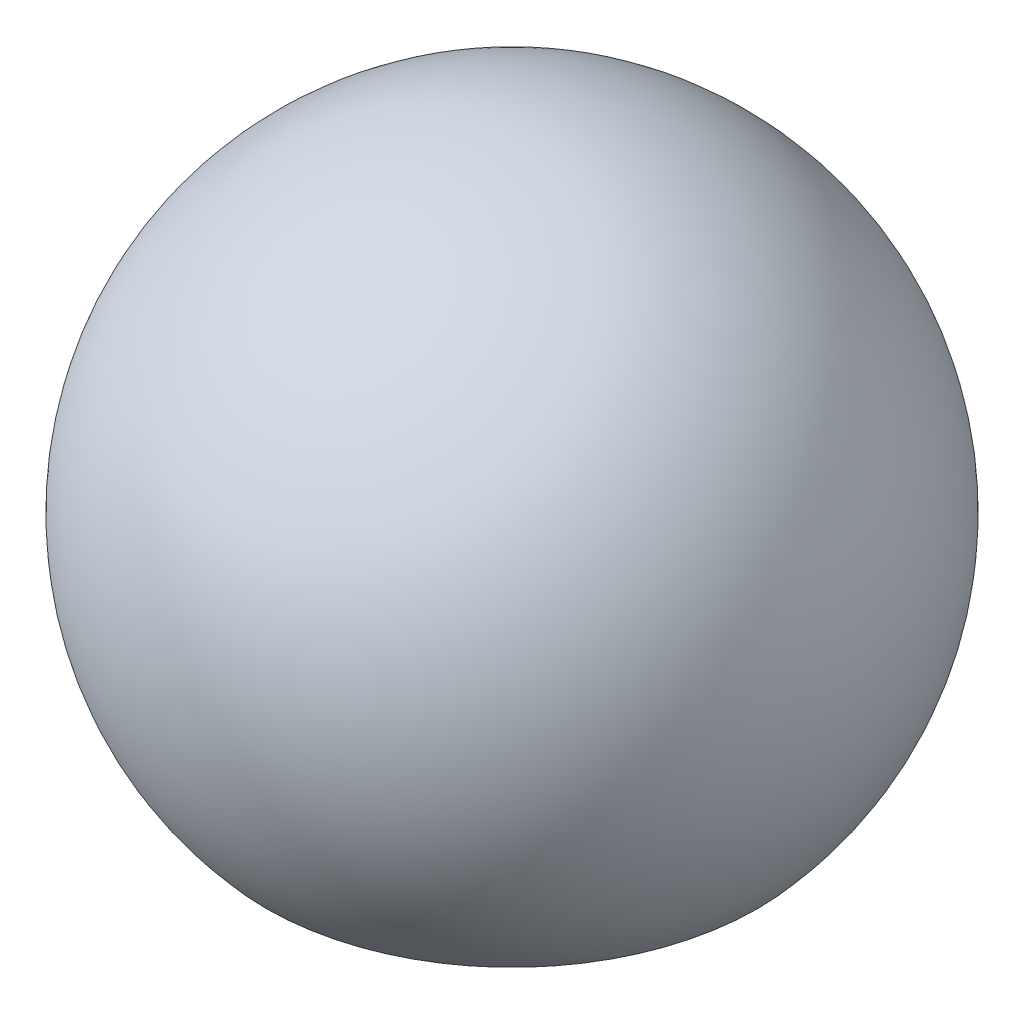
SolidWorks part; units mm, degrees
ref_plane "Front Plane" through (0, 0, 0) normal (0, 0, 1) x (1, 0, 0)
ref_plane "Top Plane" through (0, 0, 0) normal (0, 1, 0) x (1, 0, 0)
ref_plane "Right Plane" through (0, 0, 0) normal (1, 0, 0) x (0, 0, -1)
sketch "Sketch1" plane through (0, 0, 0) normal (0, 0, 1) x (1, 0, 0)
  line L0 (0, 12) -> (0, -8)
  line L1 (-12, 0) -> (12, 0) construction
  line L2 (0, 12) -> (0, -8) construction
  line L3 (0, -8) -> (8.9443, -8)
  arc A0 (8.9443, -8) -> (0, 12) centre (0, 0) ccw
  point P5 (0, 0)
  dimension "D2" = 12
  dimension "D1" = 20
revolve "Revolve1" add sketch "Sketch1" angle 360 about L0
sketch "Sketch2" plane through (0, -8, 0) normal (0, -1, 0) x (1, 0, 0)
  circle A0 centre (0, 0) radius 4
  dimension "D1" = 8
extrude "Cut-Extrude1" cut sketch "Sketch2" against normal blind 12
